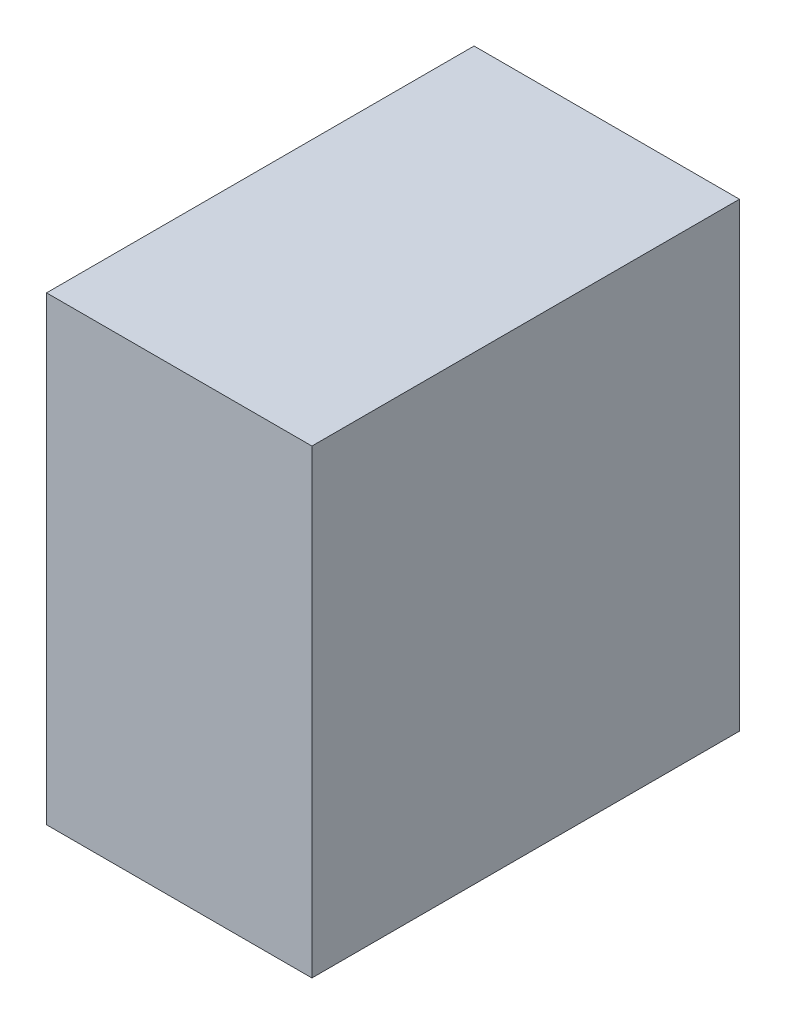
SolidWorks part; units mm, degrees
ref_plane "Front Plane" through (0, 0, 0) normal (0, 0, 1) x (1, 0, 0)
ref_plane "Top Plane" through (0, 0, 0) normal (0, 1, 0) x (1, 0, 0)
ref_plane "Right Plane" through (0, 0, 0) normal (1, 0, 0) x (0, 0, -1)
sketch "Sketch1" plane through (0, 0, 0) normal (0, 1, 0) x (1, 0, 0)
  line L1 (-180, 290) -> (180, 290)
  line L2 (-180, 290) -> (-180, -290)
  line L3 (-180, -290) -> (180, -290)
  line L4 (180, 290) -> (180, -290)
  line L5 (-180, 290) -> (180, -290) construction
  line L6 (-180, -290) -> (180, 290) construction
  point P0 (0, 0)
  dimension "D1" = 580
  dimension "D2" = 360
extrude "Boss-Extrude1" add sketch "Sketch1" along normal blind 625
